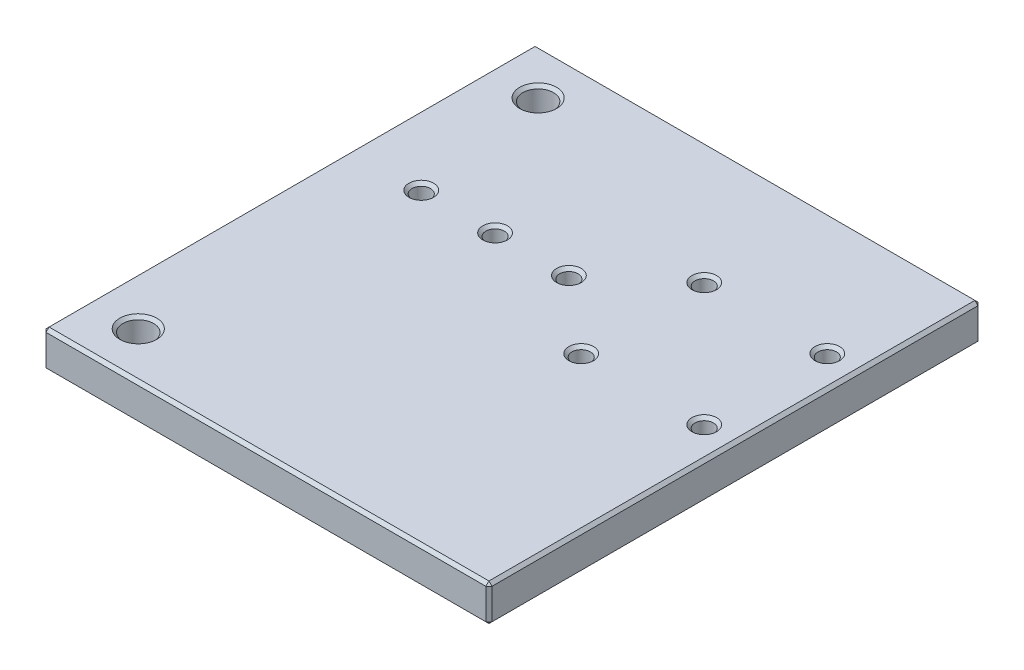
SolidWorks part; units mm, degrees
ref_plane "Alzado" through (0, 0, 0) normal (0, 0, 1) x (1, 0, 0)
ref_plane "Planta" through (0, 0, 0) normal (0, 1, 0) x (1, 0, 0)
ref_plane "Vista lateral" through (0, 0, 0) normal (1, 0, 0) x (0, 0, -1)
sketch "Croquis1" plane through (0, 0, 0) normal (0, 1, 0) x (1, 0, 0)
  line L1 (-30.519, 26.2785) -> (41.981, 26.2785)
  line L2 (-30.519, 26.2785) -> (-30.519, -53.7215)
  line L3 (-30.519, -53.7215) -> (41.981, -53.7215)
  line L4 (41.981, 26.2785) -> (41.981, -53.7215)
  circle A0 centre (16.981, 6.2785) radius 1.5
  circle A1 centre (36.981, 6.2785) radius 1.5
  circle A2 centre (16.981, -13.7215) radius 1.5
  circle A3 centre (36.981, -13.7215) radius 1.5
  circle A4 centre (-7.019, -3.7215) radius 1.5
  circle A5 centre (4.981, -3.7215) radius 1.5
  circle A6 centre (-22.519, 18.7785) radius 2.5
  circle A7 centre (-22.519, -46.2215) radius 2.5
  circle A8 centre (-19.019, -3.7215) radius 1.5
  dimension "D7" = 3
  dimension "D8" = 3
  dimension "D9" = 3
  dimension "D10" = 3
  dimension "D11" = 3
  dimension "D12" = 3
  dimension "D2" = 5
  dimension "D17" = 5
  dimension "D21" = 3
  dimension "D1" = 80
  dimension "D3" = 20
  dimension "D4" = 20
  dimension "D5" = 20
  dimension "D6" = 5
  dimension "D13" = 12
  dimension "D14" = 12
  dimension "D15" = 30
  dimension "D16" = 12
  dimension "D18" = 64.5
  dimension "D19" = 7.5
  dimension "D20" = 7.5
extrude "Saliente-Extruir1" add sketch "Croquis1" along normal blind 6
chamfer "Chaflán1" distance 0.5 angle 45 30 edges at (36.981, 0, 15.2215) (36.981, 0, -4.7785) (16.981, 0, -4.7785) (16.981, 0, 15.2215) (36.981, 6, 15.2215) (36.981, 6, -4.7785) (-30.519, 3, -26.2785) (-30.519, 3, 53.7215) (41.981, 3, 53.7215) (5.731, 0, 53.7215) (41.981, 0, 13.7215) (-30.519, 0, 13.7215) (5.731, 0, -26.2785) (41.981, 3, -26.2785) (5.731, 6, -26.2785) (41.981, 6, 13.7215) (5.731, 6, 53.7215) (-30.519, 6, 13.7215) (16.981, 6, -4.7785) (16.981, 6, 15.2215) (4.981, 0, 5.2215) (-7.019, 0, 5.2215) (4.981, 6, 5.2215) (-7.019, 6, 5.2215) (-22.519, 0, 48.7215) (-22.519, 0, -16.2785) (-22.519, 6, 48.7215) (-22.519, 6, -16.2785) (-19.019, 0, 5.2215) (-19.019, 6, 5.2215)
